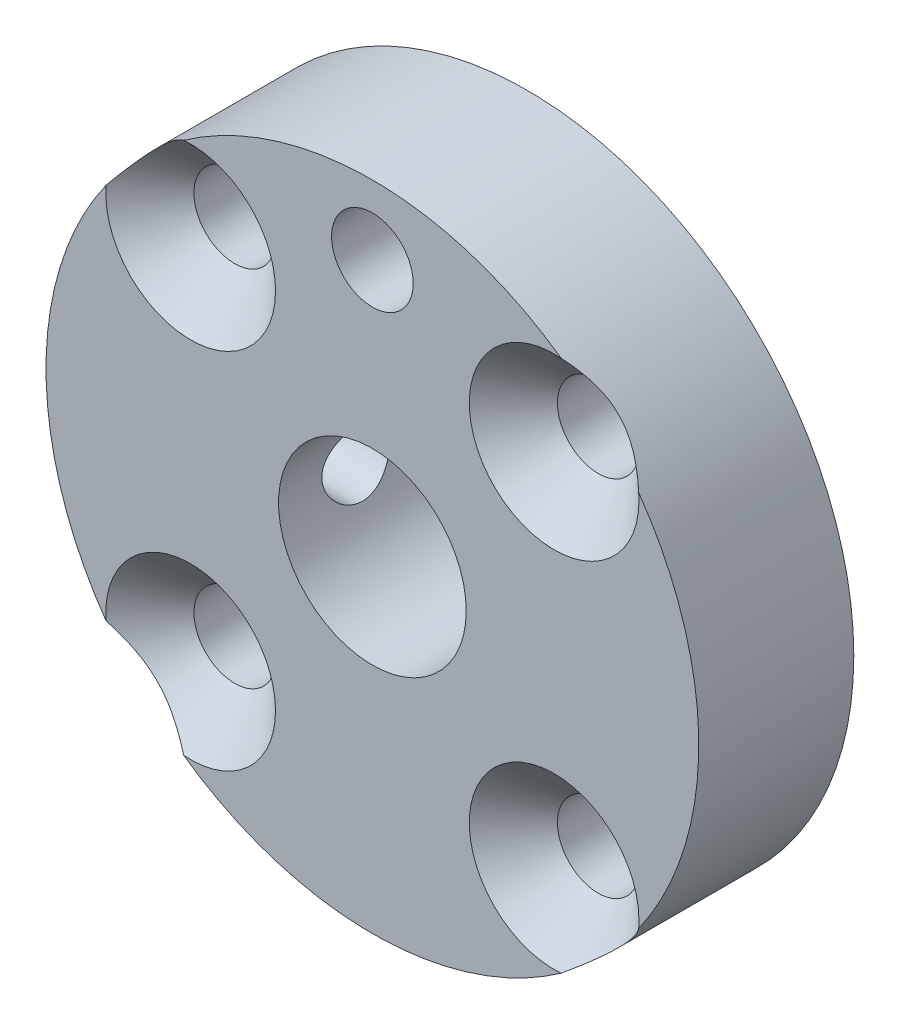
SolidWorks part; units mm, degrees
material "Nylon 101"
ref_plane "Front Plane" through (0, 0, 0) normal (0, 0, 1) x (1, 0, 0)
ref_plane "Top Plane" through (0, 0, 0) normal (0, 1, 0) x (1, 0, 0)
ref_plane "Right Plane" through (0, 0, 0) normal (1, 0, 0) x (0, 0, -1)
sketch "Sketch1" plane through (0, 0, 0) normal (0, 0, 1) x (1, 0, 0)
  circle A0 centre (0, 0) radius 20
  circle A1 centre (0, 15.75) radius 2.5
  circle A2 centre (11.1369, 11.1369) radius 2
  circle A3 centre (0, 0) radius 15.75 construction
  circle A4 centre (11.1369, -11.1369) radius 2
  circle A5 centre (-11.1369, -11.1369) radius 2
  circle A6 centre (-11.1369, 11.1369) radius 2
  circle A7 centre (0, 0) radius 10
  point P17 (0, 0)
  dimension "D1" = 40
  dimension "D2" = 31.5
  dimension "D3" = 5
  dimension "D4" = 4
  dimension "D7" = 20
  dimension "D5" = 45
  dimension "D6" = 4
sketch "Sketch2" plane through (0, 0, 0) normal (0, 0, 1) x (1, 0, 0)
  circle A1 centre (0, 0) radius 20 construction
  circle A3 centre (0, 0) radius 20
extrude "Boss-Extrude1" add sketch "Sketch2" along normal blind 9.5
hole_wizard "CSK for M5 Flat Head Machine Screw1" positions "Sketch3" profile "Sketch4" countersink size "M5" standard "ANSI Metric" end condition through all
sketch "Sketch3" plane through (0, 0, 9.5) normal (0, 0, 1) x (1, 0, 0)
  point P0 (-11.1369, 11.1369)
  point P6 (11.1369, 11.1369)
  point P9 (11.1369, -11.1369)
  point P12 (-11.1369, -11.1369)
  point P16 (0, 0)
sketch "Sketch4" plane through (-11.1369, 11.1369, 9.5) normal (1, 0, 0) x (0, -1, 0)
  line L0 (0, 0) -> (0, 9.5)
  line L1 (0, 9.5) -> (2.5, 9.5)
  line L2 (2.5, 9.5) -> (2.5, 2.7)
  line L3 (2.5, 2.7) -> (5.2, 0)
  line L5 (5.2, 0) -> (0, 0)
  line L6 (-2.5, 2.7) -> (-5.2, 0) construction
  line L11 (0, -6.35) -> (0, 107.95) construction
  dimension "Thru Hole Dia." = 5
  dimension "Thru Hole Depth" = 9.5
  dimension "Near C'Sink Dia." = 10.4
  dimension "Near C'Sink Angle" = 90
sketch "Sketch5" plane through (0, 0, 9.5) normal (0, 0, 1) x (1, 0, 0)
  circle A0 centre (0, 15.75) radius 2.5 construction
  circle A1 centre (0, 15.75) radius 2.5
extrude "Cut-Extrude1" cut sketch "Sketch5" against normal through all
sketch "Sketch6" plane through (0, 0, 9.5) normal (0, 0, 1) x (1, 0, 0)
  circle A0 centre (0, 0) radius 5.75
  dimension "D1" = 11.5
extrude "Cut-Extrude2" cut sketch "Sketch6" against normal through all
sketch "Sketch8" plane through (0, 0, 0) normal (1, 0, 0) x (0, 0, -1)
  line L0 (-9.5, 0) -> (0, 0) construction
  line L1 (-9.5, 11.5617) -> (-9.5, -11.5617) construction
  circle A0 centre (-4.75, 0) radius 2.1
  point P7 (0, 0)
  dimension "D1" = 4.2
extrude "Cut-Extrude3" cut sketch "Sketch8" against normal through all
sketch "Sketch9" plane through (0, 0, 0) normal (0, 1, 0) x (1, 0, 0)
  line L0 (-0.4, -2.8232) -> (0, -2.1304) construction
  line L1 (0, -2.1304) -> (0.4, -2.8232) construction
  line L2 (0.4, -2.8232) -> (-0.4, -2.8232)
  line L3 (0.4, -2.8232) -> (0.8, -2.1304) construction
  line L4 (0.8, -2.1304) -> (1.2, -2.8232) construction
  line L5 (1.2, -2.8232) -> (0.4, -2.8232) construction
  line L7 (-0.2, -2.4768) -> (0.2, -2.4768) construction
  line L8 (0.2, -2.4768) -> (0.6, -2.4768) construction
  line L9 (0.6, -2.4768) -> (1, -2.4768) construction
  line L10 (-0.05, -2.217) -> (0.05, -2.217)
  line L11 (-0.4, -2.8232) -> (-0.05, -2.217)
  line L12 (0.05, -2.217) -> (0.4, -2.8232)
  line L13 (0.3, -2.65) -> (0.5, -2.65) construction
  point P2 (-19.2832, -2.65)
  point P11 (0, 0)
  point P12 (0, 0)
  point P14 (-20, -2.65)
  point P19 (0, 0)
  dimension "D1" = 60
  dimension "D2" = 0.8
  dimension "D3" = 0.1
  dimension "D4" = 0.2
sketch "Sketch10" plane through (0, 0, 0) normal (1, 0, 0) x (0, 0, -1)
  circle A1 centre (-4.75, 0) radius 2.1
  circle A2 centre (-4.75, 0) radius 2.1 construction
curve "Helix/Spiral1" pitch 0.8 height 20 turns 25
hole_wizard "CBORE for M5 Hex Head Cap Screw1" positions "3DSketch2" profile "Sketch18" counterbore size "M5" standard "ANSI Metric"
sketch3d "3DSketch2"
  line L1 (0, 0, 4.75) -> (-20, 0, 4.75) construction
  line L3 (0, 0, 0) -> (0, 0, 9.5) construction
  point P0 (-20, 0, 4.75)
  point P12 (0, 0, 12.2556)
  point P13 (0, 0, 0)
  point P23 (0, 0, 0)
  point P24 (0, 0, 10.6148)
sketch "Sketch18" plane through (-20, 0, 4.75) normal (0, 1, 0) x (0, 0, 1)
  line L0 (0, 0) -> (0, 14.25)
  line L1 (0, 14.25) -> (2.75, 14.25)
  line L3 (2.75, 14.25) -> (2.75, 3.65)
  line L4 (2.75, 3.65) -> (6.12, 3.65)
  line L5 (6.12, 3.65) -> (6.12, 0)
  line L7 (6.12, 0) -> (0, 0)
  line L11 (0, -6.35) -> (0, 107.95) construction
  dimension "Thru Hole Dia." = 5.5
  dimension "Thru Hole Depth" = 14.25
  dimension "C'Bore Dia." = 12.24
  dimension "C'Bore Depth" = 3.65
